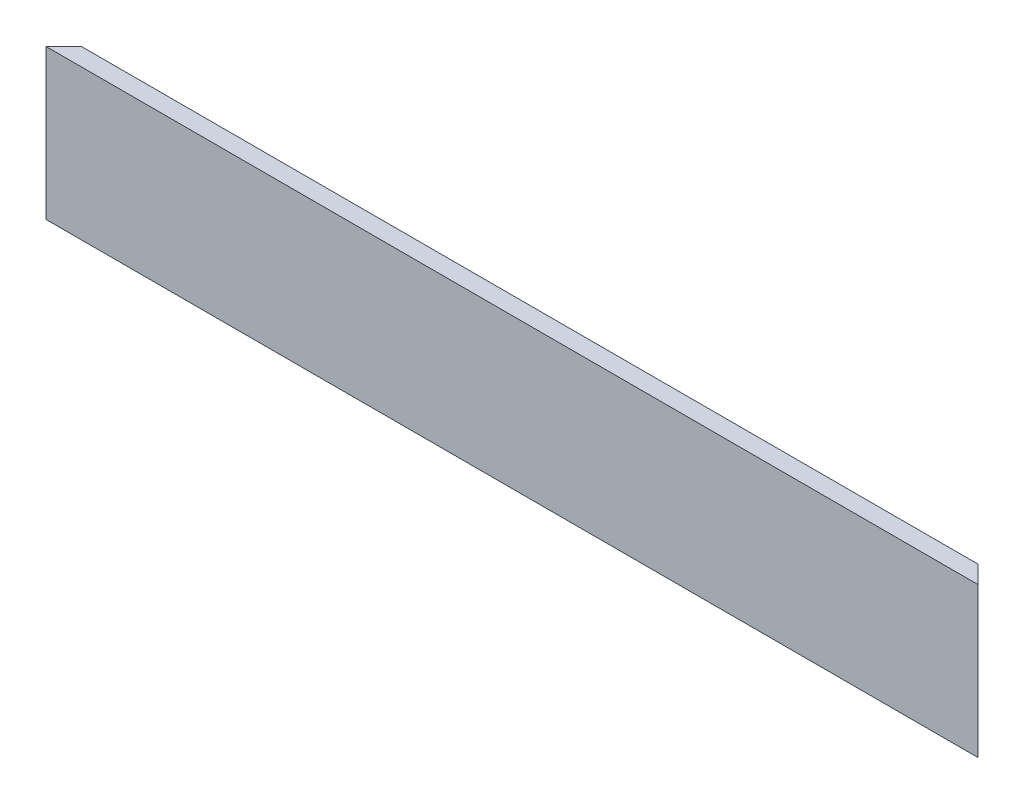
SolidWorks part; units mm, degrees
material "0.6010 (EN-GJL-100)"
ref_plane "Alzado" through (0, 0, 0) normal (0, 0, 1) x (1, 0, 0)
ref_plane "Planta" through (0, 0, 0) normal (0, 1, 0) x (1, 0, 0)
ref_plane "Vista lateral" through (0, 0, 0) normal (1, 0, 0) x (0, 0, -1)
sketch "Croquis1" plane through (0, 0, 0) normal (1, 0, 0) x (0, 0, -1)
  line L0 (-16.8743, 6.35) -> (-16.8743, -19.05)
  line L1 (-16.8743, -19.05) -> (8.5257, -19.05)
  line L2 (8.5257, -19.05) -> (8.5257, -16.05)
  line L3 (8.5257, -16.05) -> (-13.8743, -16.05)
  line L4 (-13.8743, -16.05) -> (-13.8743, 6.35)
  line L5 (-16.8743, 6.35) -> (-13.8743, 6.35)
  dimension "D1" = 25.4
  dimension "D2" = 3
  dimension "D3" = 3
  dimension "D4" = 25.4
extrude "Saliente-Extruir1" add sketch "Croquis1" along normal blind 158
sketch "Croquis3" plane through (0, 6.35, 0) normal (0, 1, 0) x (1, 0, 0)
  line L0 (0, -16.8743) -> (25.4, 8.5257)
  line L1 (158, 8.5257) -> (0, 8.5257) construction
  line L2 (25.4, 8.5257) -> (0, 8.5257)
  line L3 (0, 8.5257) -> (0, -16.8743)
  dimension "D1" = 45
extrude "Cortar-Extruir3" cut sketch "Croquis3" against normal blind 105
sketch "Croquis4" plane through (0, 6.35, 0) normal (0, 1, 0) x (1, 0, 0)
  line L0 (158, -16.8743) -> (158, 8.5257)
  line L1 (158, 8.5257) -> (132.6, 8.5257)
  line L2 (158, 8.5257) -> (25.4, 8.5257) construction
  line L3 (132.6, 8.5257) -> (158, -16.8743)
  dimension "D1" = 45
extrude "Cortar-Extruir4" cut sketch "Croquis4" against normal blind 105
